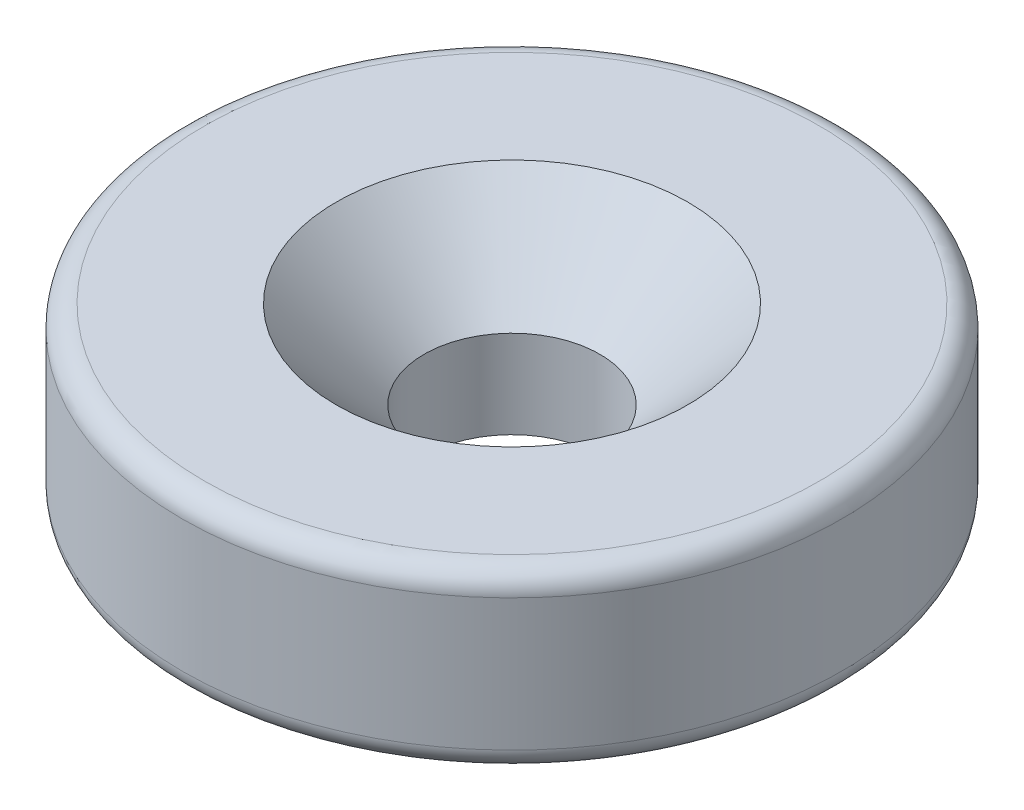
SolidWorks part; units mm, degrees
ref_plane "Front Plane" through (0, 0, 0) normal (0, 0, 1) x (1, 0, 0)
ref_plane "Top Plane" through (0, 0, 0) normal (0, 1, 0) x (1, 0, 0)
ref_plane "Right Plane" through (0, 0, 0) normal (1, 0, 0) x (0, 0, -1)
sketch "Sketch1" plane through (0, 0, 0) normal (0, 1, 0) x (1, 0, 0)
  circle A0 centre (0, 0) radius 7.5
  circle A1 centre (0, 0) radius 2
  dimension "D1" = 15
  dimension "D2" = 4
extrude "Boss-Extrude1" add sketch "Sketch1" along normal mid plane 4
fillet "Fillet1" radius 0.5 2 edges at (0, -2, 7.5) (0, 2, 7.5)
chamfer "Chamfer1" distance 2 angle 45 1 edges at (0, 2, 2)
